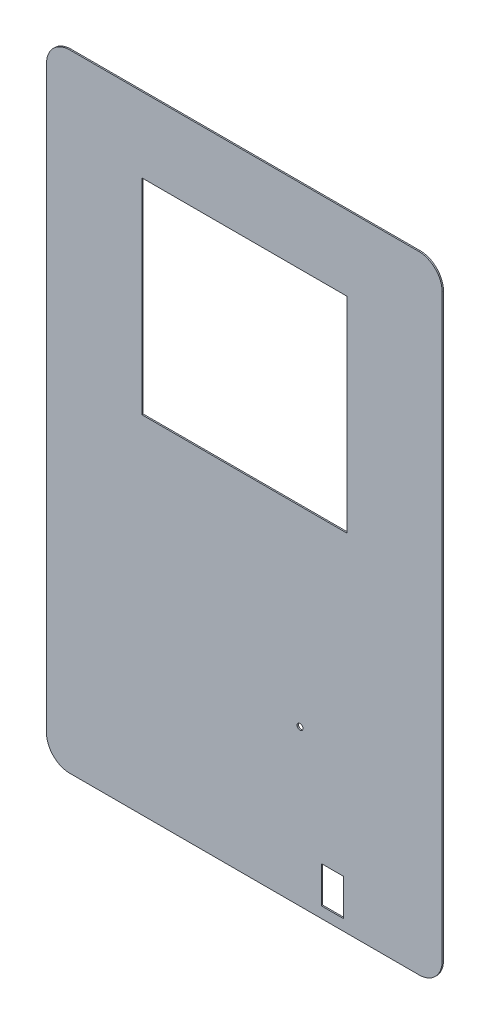
SolidWorks part; units mm, degrees
ref_plane "前视基准面" through (0, 0, 0) normal (0, 0, 1) x (1, 0, 0)
ref_plane "上视基准面" through (0, 0, 0) normal (0, 1, 0) x (1, 0, 0)
ref_plane "右视基准面" through (0, 0, 0) normal (1, 0, 0) x (0, 0, -1)
sketch "草图1" plane through (0, 0, 0) normal (0, 0, 1) x (1, 0, 0)
  line L1 (-23.82, -42.75) -> (23.82, -42.75)
  line L2 (-27, -39.57) -> (-27, 39.57)
  line L3 (-23.82, 42.75) -> (23.82, 42.75)
  line L4 (27, -39.57) -> (27, 39.57)
  line L5 (-27, -42.75) -> (27, 42.75) construction
  line L6 (-27, 42.75) -> (27, -42.75) construction
  arc A0 (-23.82, -42.75) -> (-27, -39.57) centre (-23.82, -39.57) cw
  arc A1 (23.82, -42.75) -> (27, -39.57) centre (23.82, -39.57) ccw
  arc A2 (23.82, 42.75) -> (27, 39.57) centre (23.82, 39.57) cw
  arc A3 (-27, 39.57) -> (-23.82, 42.75) centre (-23.82, 39.57) cw
  point P0 (0, 0)
  dimension "D3" = 3.18
  dimension "D1" = 54
  dimension "D2" = 85.5
extrude "凸台-拉伸1" add sketch "草图1" along normal blind 0.18
sketch "草图2" plane through (0, 0, 0.18) normal (0, 0, 1) x (1, 0, 0)
  line L0 (27, -39.57) -> (27, 39.57) construction
  line L1 (10.5, -41.25) -> (13.5, -41.25)
  line L2 (10.5, -41.25) -> (10.5, -36.25)
  line L3 (10.5, -36.25) -> (13.5, -36.25)
  line L4 (13.5, -41.25) -> (13.5, -36.25)
  line L5 (10.5, -41.25) -> (13.5, -36.25) construction
  line L6 (10.5, -36.25) -> (13.5, -41.25) construction
  line L7 (-23.82, -42.75) -> (23.82, -42.75) construction
  circle A0 centre (7.6, -21.55) radius 0.4
  point P0 (12, -38.75)
  dimension "D5" = 0.8
  dimension "D1" = 3
  dimension "D2" = 5
  dimension "D3" = 13.5
  dimension "D4" = 1.5
  dimension "D6" = 19.4
  dimension "D7" = 21.2
extrude "切除-拉伸1" cut sketch "草图2" against normal up to next
sketch "草图3" plane through (0, 0, 0.18) normal (0, 0, 1) x (1, 0, 0)
  line L0 (23.82, 42.75) -> (-23.82, 42.75) construction
  line L1 (-14, 32.55) -> (14, 32.55)
  line L2 (-14, 32.55) -> (-14, 4.55)
  line L3 (-14, 4.55) -> (14, 4.55)
  line L4 (14, 32.55) -> (14, 4.55)
  line L5 (-14, 32.55) -> (14, 4.55) construction
  line L6 (-14, 4.55) -> (14, 32.55) construction
  point P0 (0, 18.55)
  dimension "D1" = 28
  dimension "D2" = 28
  dimension "D3" = 10.2
extrude "切除-拉伸2" cut sketch "草图3" against normal blind 0.18
